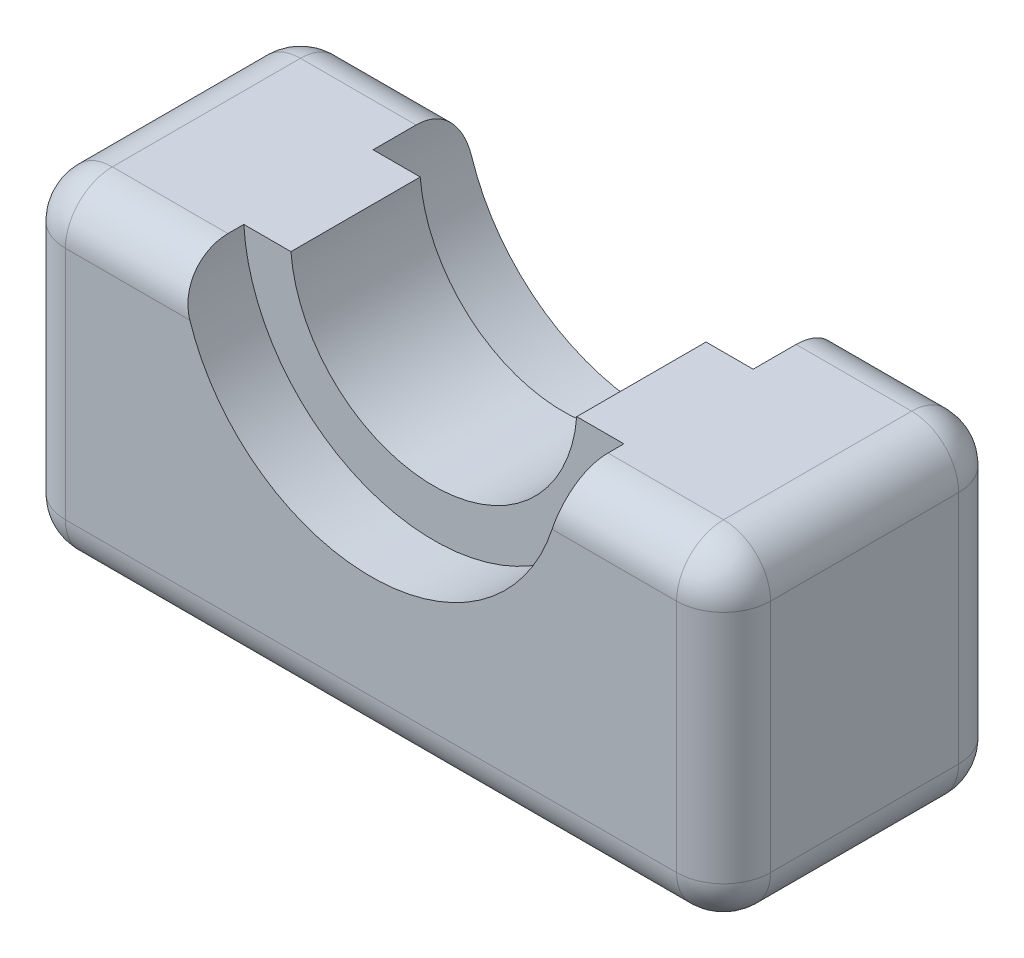
SolidWorks part; units mm, degrees
ref_plane "Спереди" through (0, 0, 0) normal (0, 0, 1) x (1, 0, 0)
ref_plane "Сверху" through (0, 0, 0) normal (0, 1, 0) x (1, 0, 0)
ref_plane "Справа" through (0, 0, 0) normal (1, 0, 0) x (0, 0, -1)
sketch "Эскиз1" plane through (0, 0, 0) normal (0, 0, 1) x (1, 0, 0)
  line L1 (-15, -7) -> (15, -7)
  line L2 (-15, -7) -> (-15, 7)
  line L3 (-15, 7) -> (15, 7)
  line L4 (15, -7) -> (15, 7)
  line L5 (-15, -7) -> (15, 7) construction
  line L6 (-15, 7) -> (15, -7) construction
  point P0 (0, 0)
  dimension "D1" = 14
  dimension "D2" = 30
extrude "Бобышка-Вытянуть1" add sketch "Эскиз1" along normal blind 12
ref_plane "Плоскость1" through (0, 7.5, 0) normal (0, 1, 0) x (1, 0, 0)
sketch "Эскиз2" plane through (0, 7.5, 0) normal (0, 1, 0) x (1, 0, 0)
  line L0 (0, 4.4138) -> (0, -16.522) construction
  line L1 (0, 0) -> (0, -12)
  line L2 (15, -12) -> (-15, -12) construction
  line L3 (0, -12) -> (8.1, -12)
  line L4 (8.1, -12) -> (8.1, -9.325)
  line L5 (8.1, -9.325) -> (6.1, -9.325)
  line L6 (6.1, -9.325) -> (6.1, -3.825)
  line L7 (6.1, -3.825) -> (8.1, -3.825)
  line L8 (8.1, -3.825) -> (8.1, 0)
  line L9 (15, 0) -> (-15, 0) construction
  line L10 (0, 0) -> (8.1, 0)
  dimension "D1" = 5.5
  dimension "D2" = 2.675
  dimension "D3" = 12.2
  dimension "D4" = 16.2
revolve "Вырез-Повернуть1" cut sketch "Эскиз2" angle 360 about L0
fillet "Скругление1" radius 2 14 edges at (-15, -7, 6) (0, -7, 0) (15, -7, 6) (0, -7, 12) (11.5423, 7, 12) (-11.5423, 7, 12) (-11.5423, 7, 0) (11.5423, 7, 0) (15, 0, 12) (15, 0, 0) (-15, 0, 12) (-15, 0, 0) (-15, 7, 6) (15, 7, 6)
